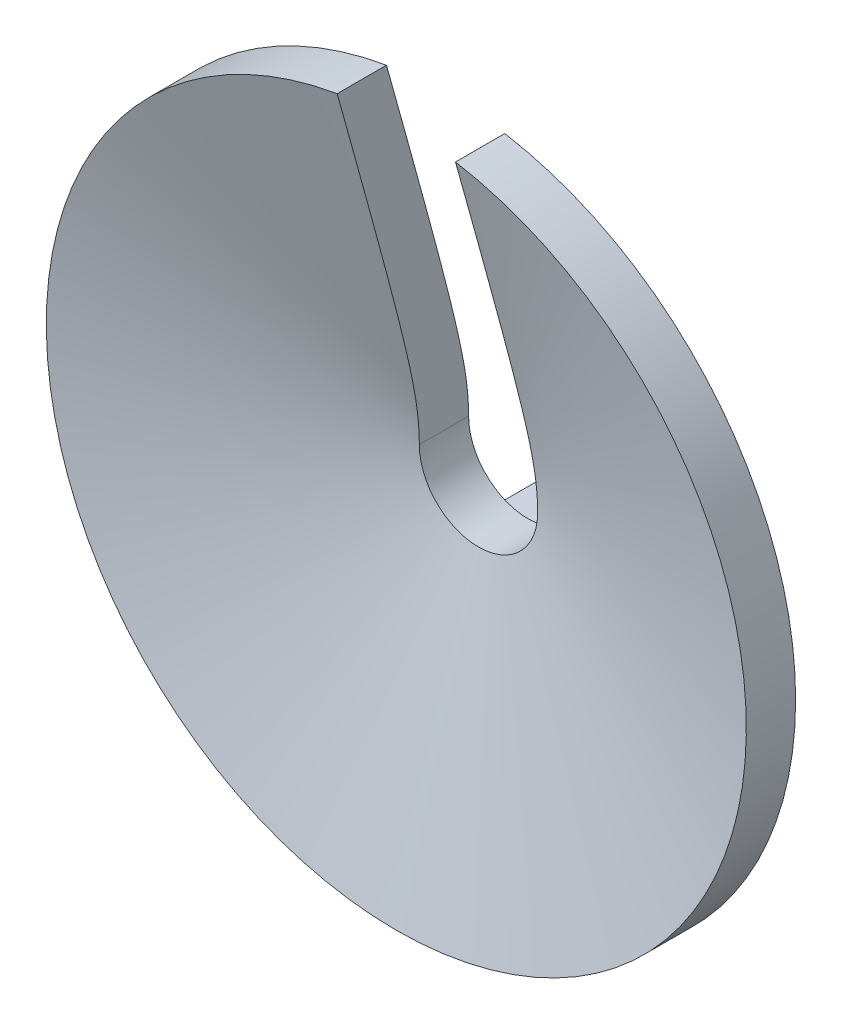
SolidWorks part; units mm, degrees
ref_plane "Front Plane" through (0, 0, 0) normal (0, 0, 1) x (1, 0, 0)
ref_plane "Top Plane" through (0, 0, 0) normal (0, 1, 0) x (1, 0, 0)
ref_plane "Right Plane" through (0, 0, 0) normal (1, 0, 0) x (0, 0, -1)
sketch "Sketch1" plane through (0, 0, 0) normal (0, 0, 1) x (1, 0, 0)
  circle A0 centre (0, 0) radius 35.5
  dimension "D1" = 71
extrude "Boss-Extrude1" add sketch "Sketch1" along normal blind 15
sketch "Sketch2" plane through (0, 0, 0) normal (0, 1, 0) x (1, 0, 0)
  line L0 (-0.1, 0) -> (-35.5, -10)
  line L2 (-35.5, -10) -> (-35.5, 0)
  line L4 (-35.5, 0) -> (-0.1, 0)
  line L5 (-35.5, -15) -> (-0.1, -15)
  line L6 (35.5, 0) -> (-35.5, 0) construction
  line L7 (-0.1, -15) -> (-0.1, -5)
  line L8 (-0.1, -5) -> (-35.5, -15)
  line L9 (-35.5, -15) -> (35.5, -15) construction
  line L11 (0, 0) -> (0, -21.6488) construction
  line L12 (-35.5, 0) -> (-35.5, -15) construction
  dimension "D1" = 10
  dimension "D2" = 0.1
revolve "Cut-Revolve3" cut sketch "Sketch2" angle 360 about L11
sketch "Sketch3" plane through (0, 0, 0) normal (0, 0, 1) x (1, 0, 0)
  line L0 (0, 35.5) -> (0, 0) construction
  line L1 (6, 35.5) -> (6, 0)
  line L2 (-6, 35.5) -> (-6, 0)
  circle A0 centre (0, 0) radius 35.5 construction
  arc A1 (6, 35.5) -> (-6, 35.5) centre (0, 35.5) ccw
  arc A2 (-6, 0) -> (6, 0) centre (0, 0) ccw
  point P5 (0, 17.75)
  dimension "D1" = 6
extrude "Cut-Extrude2" cut sketch "Sketch3" along normal up to next
sketch "Sketch4" plane through (0, 0, 0) normal (0, 0, 1) x (1, 0, 0)
  line L1 (-8.175, -9.3709) -> (8.175, -9.3709)
  line L2 (-8.175, -9.3709) -> (-8.175, -34.5459)
  line L4 (8.175, -9.3709) -> (8.175, -34.5459)
  arc A0 (-6, 34.9893) -> (6, 34.9893) centre (0, 0) ccw construction
  arc A1 (-8.175, -34.5459) -> (8.175, -34.5459) centre (0, 0) ccw
  point P4 (0, 0)
  point P8 (0, 0)
  dimension "D1" = 16.35
  dimension "D2" = 25.175
extrude "Boss-Extrude2" add sketch "Sketch4" along normal up to next from offset 10 offset against normal yes
sketch "Sketch5" plane through (0, 0, 0) normal (0, 1, 0) x (1, 0, 0)
  line L0 (-35.5, -10) -> (-6, -10) construction
  line L1 (-5.25, 5.5) -> (5.25, 5.5)
  line L2 (-5.25, 5.5) -> (-5.25, 0)
  line L3 (-5.25, 0) -> (5.25, 0)
  line L4 (5.25, 5.5) -> (5.25, 0)
  point P4 (0, 0)
  dimension "D1" = 10.5
  dimension "D2" = 5.5
  dimension "D3" = 10
extrude "Cut-Extrude3" cut sketch "Sketch5" along normal blind 22 from offset 36 offset against normal yes
chamfer "Chamfer1" distance 0.6 angle 45 4 edges at (-5.25, -24.5548, -5.5) (-5.25, -24.5548, 0) (5.25, -24.5548, 0) (5.25, -24.5548, -5.5)
chamfer "Chamfer2" distance 2 angle 45 5 edges at (8.175, -9.3709, -3.2577) (-8.175, -9.3709, -3.2577) (8.175, -21.9584, -10) (0, -9.3709, -10) (-8.175, -21.9584, -10)
sketch "Sketch6" plane through (0, 0, -10) normal (0, 0, -1) x (-1, 0, 0)
  line L0 (4.65, -14) -> (-4.65, -14) construction
  circle A0 centre (0, -21) radius 3
  dimension "D1" = 6
  dimension "D2" = 7
extrude "Cut-Extrude4" cut sketch "Sketch6" against normal up to next
